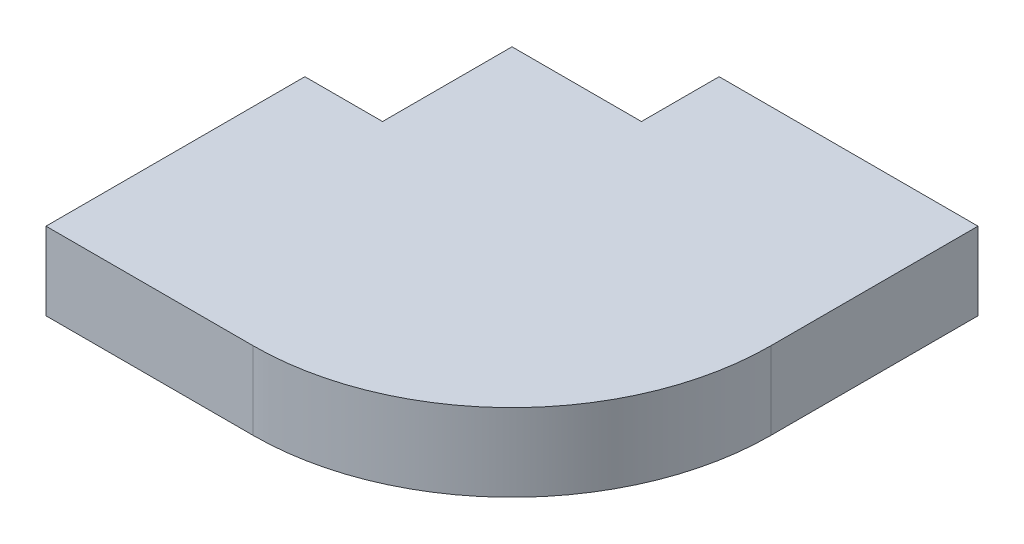
SolidWorks part; units mm, degrees
ref_plane "Front Plane" through (0, 0, 0) normal (0, 0, 1) x (1, 0, 0)
ref_plane "Top Plane" through (0, 0, 0) normal (0, 1, 0) x (1, 0, 0)
ref_plane "Right Plane" through (0, 0, 0) normal (1, 0, 0) x (0, 0, -1)
sketch "Sketch1" plane through (0, 0, 0) normal (0, 1, 0) x (1, 0, 0)
  line L5 (-7.5, 2.5) -> (-10.5, 2.5)
  line L6 (-7.5, -7.5) -> (-2.5, -7.5)
  line L16 (-7.5, 2.5) -> (-7.5, 7.5)
  line L23 (-7.5, 7.5) -> (-2.5, 7.5)
  line L34 (7.5, 2.5) -> (7.5, 7.5)
  line L37 (-10.5, 2.5) -> (-10.5, -7.5)
  line L38 (-10.5, -7.5) -> (-7.5, -7.5)
  line L39 (-2.5, 7.5) -> (-2.5, 10.5)
  line L40 (-2.5, 10.5) -> (7.5, 10.5)
  line L41 (7.5, 10.5) -> (7.5, 7.5)
  arc A3 (-2.5, -7.5) -> (7.5, 2.5) centre (-2.5, 2.5) ccw
  point P0 (0, 0)
  point P4 (0, 0)
extrude "Boss-Extrude1" add sketch "Sketch1" along normal blind 3
